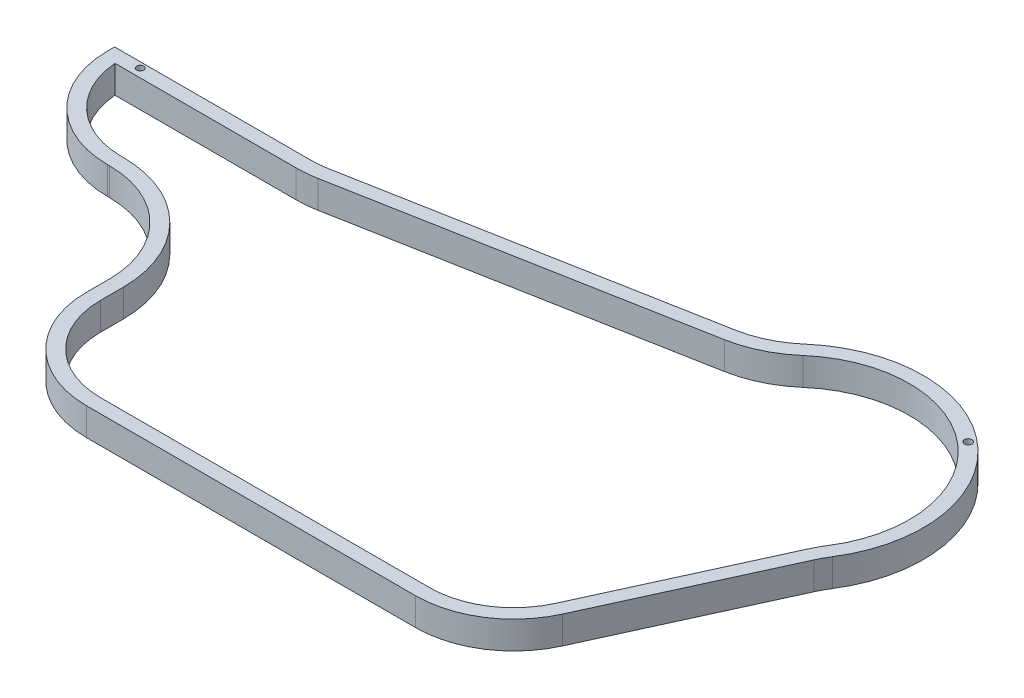
SolidWorks part; units mm, degrees
ref_plane "Front Plane" through (0, 0, 0) normal (0, 0, 1) x (1, 0, 0)
ref_plane "Top Plane" through (0, 0, 0) normal (0, 1, 0) x (1, 0, 0)
ref_plane "Right Plane" through (0, 0, 0) normal (1, 0, 0) x (0, 0, -1)
sketch "Sketch1" plane through (0, 0, 0) normal (0, 1, 0) x (1, 0, 0)
  line L0 (-0.5598, 25.0793) -> (-35.8905, 25.0793)
  line L1 (-35.8905, 25.0793) -> (-35.8905, 23.7772)
  line L2 (-18.1105, 5.9972) -> (-17.78, 5.9972)
  line L3 (0, -11.7828) -> (0, -15.9135)
  line L4 (17.78, -33.6935) -> (77.3127, -33.6935)
  line L5 (2.6808, 25.3771) -> (64.6604, 36.8661)
  line L6 (93.488, -23.2951) -> (107.7686, 7.9979)
  arc A0 (108.9207, 10.1259) -> (73.0806, 40.9261) centre (88.7426, 22.8985) ccw
  arc A1 (-35.8905, 23.7772) -> (-18.1105, 5.9972) centre (-18.1105, 23.7772) ccw
  arc A2 (0, -15.9135) -> (17.78, -33.6935) centre (17.78, -15.9135) ccw
  arc A3 (77.3127, -33.6935) -> (93.488, -23.2951) centre (77.3127, -15.9135) ccw
  arc A4 (107.7686, 7.9979) -> (108.9207, 10.1259) centre (123.9439, 0.6163) cw
  arc A5 (64.6604, 36.8661) -> (73.0806, 40.9261) centre (61.4198, 54.3482) ccw
  arc A6 (-0.5598, 25.0793) -> (2.6808, 25.3771) centre (-0.5598, 42.8593) ccw
  arc A7 (-17.78, 5.9972) -> (0, -11.7828) centre (-17.78, -11.7828) cw
  dimension "D1" = 17.78
extrude "Boss-Extrude1" add sketch "Sketch1" along normal blind 5
sketch "Sketch2" plane through (0, 5, 0) normal (0, 1, 0) x (1, 0, 0)
  line L7 (64.6604, 36.8661) -> (2.6808, 25.3771) construction
  line L14 (-18.1105, 8.5372) -> (-17.78, 8.5372)
  line L15 (2.54, -11.7828) -> (2.54, -15.9135)
  line L16 (17.78, -31.1535) -> (77.3127, -31.1535)
  line L17 (91.1772, -22.2406) -> (105.4579, 9.0524)
  line L18 (65.1233, 34.3686) -> (3.1437, 22.8797)
  line L19 (-0.5598, 22.5393) -> (-33.3002, 22.5393)
  line L20 (-18.1105, 8.5372) -> (-17.78, 8.5372)
  line L21 (2.54, -11.7828) -> (2.54, -15.9135)
  line L22 (17.78, -31.1535) -> (77.3127, -31.1535)
  line L23 (91.1772, -22.2406) -> (105.4579, 9.0524)
  line L24 (65.1233, 34.3686) -> (3.1437, 22.8797)
  line L25 (-0.5598, 22.5393) -> (-33.3002, 22.5393)
  arc A16 (-33.3002, 22.5393) -> (-18.1105, 8.5372) centre (-18.1105, 23.7772) ccw
  arc A17 (2.54, -11.7828) -> (-17.78, 8.5372) centre (-17.78, -11.7828) ccw
  arc A18 (2.54, -15.9135) -> (17.78, -31.1535) centre (17.78, -15.9135) ccw
  arc A19 (77.3127, -31.1535) -> (91.1772, -22.2406) centre (77.3127, -15.9135) ccw
  arc A20 (106.7746, 11.4844) -> (105.4579, 9.0524) centre (123.9439, 0.6163) ccw
  arc A21 (106.7746, 11.4844) -> (74.7464, 39.0087) centre (88.7426, 22.8985) ccw
  arc A22 (65.1233, 34.3686) -> (74.7464, 39.0087) centre (61.4198, 54.3482) ccw
  arc A23 (-0.5598, 22.5393) -> (3.1437, 22.8797) centre (-0.5598, 42.8593) ccw
  arc A24 (-33.3002, 22.5393) -> (-18.1105, 8.5372) centre (-18.1105, 23.7772) ccw
  arc A25 (2.54, -11.7828) -> (-17.78, 8.5372) centre (-17.78, -11.7828) ccw
  arc A26 (2.54, -15.9135) -> (17.78, -31.1535) centre (17.78, -15.9135) ccw
  arc A27 (77.3127, -31.1535) -> (91.1772, -22.2406) centre (77.3127, -15.9135) ccw
  arc A28 (106.7746, 11.4844) -> (105.4579, 9.0524) centre (123.9439, 0.6163) ccw
  arc A29 (106.7746, 11.4844) -> (74.7464, 39.0087) centre (88.7426, 22.8985) ccw
  arc A30 (65.1233, 34.3686) -> (74.7464, 39.0087) centre (61.4198, 54.3482) ccw
  arc A31 (-0.5598, 22.5393) -> (3.1437, 22.8797) centre (-0.5598, 42.8593) ccw
  dimension "D2" = 2.54
  dimension "D1" = 2.54
extrude "Cut-Extrude2" cut sketch "Sketch2" against normal blind 8.048
sketch "Sketch3" plane through (0, 5, 0) normal (0, 1, 0) x (1, 0, 0)
  circle A0 centre (-30.2612, 24.0772) radius 0.6409
  circle A1 centre (103.2094, 40.4267) radius 0.6832
extrude "Cut-Extrude3" cut sketch "Sketch3" against normal blind 8.048
